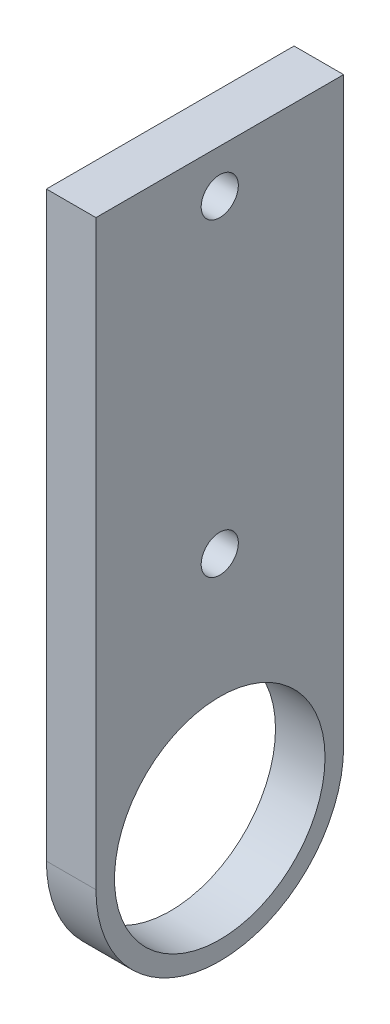
SolidWorks part; units mm, degrees
ref_plane "前视基准面" through (0, 0, 0) normal (0, 0, 1) x (1, 0, 0)
ref_plane "上视基准面" through (0, 0, 0) normal (0, 1, 0) x (1, 0, 0)
ref_plane "右视基准面" through (0, 0, 0) normal (1, 0, 0) x (0, 0, -1)
sketch "草图1" plane through (0, 0, 0) normal (1, 0, 0) x (0, 0, -1)
  line L0 (0, 26) -> (0, 22.5) construction
  line L1 (-10, 26) -> (-10, -21)
  line L2 (10, 26) -> (10, -21)
  line L3 (10, 26) -> (-10, 26)
  line L4 (0, -31) -> (0, -21)
  line L5 (10, -26) -> (-10, 26) construction
  line L6 (10, 26) -> (-10, -26) construction
  line L8 (0, 22.5) -> (0, -2.5)
  circle A0 centre (0, 22.5) radius 1.5
  circle A1 centre (0, -21) radius 8.5
  arc A2 (-10, -21) -> (10, -21) centre (0, -21) ccw
  circle A3 centre (0, -2.5) radius 1.5
  point P0 (0, 0)
  dimension "D4" = 10
  dimension "D5" = 25
  dimension "D6" = 47
  dimension "D1" = 20
  dimension "D2" = 52
  dimension "D3" = 3.5
extrude "凸台-拉伸1" add sketch "草图1" along normal blind 4
